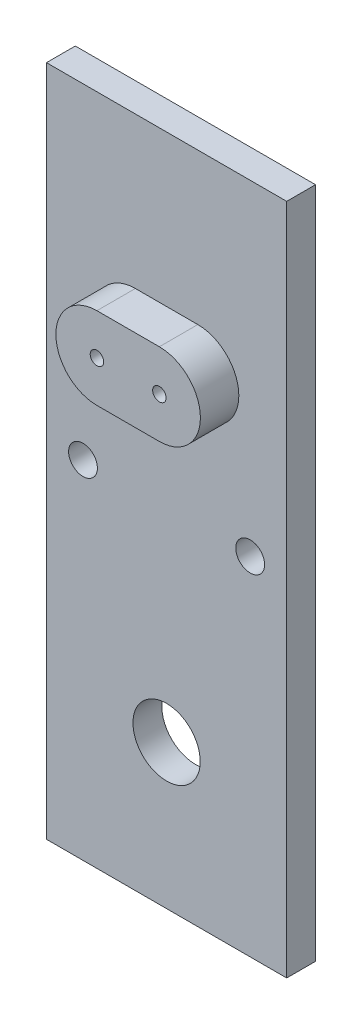
SolidWorks part; units mm, degrees
ref_plane "Front Plane" through (0, 0, 0) normal (0, 0, 1) x (1, 0, 0)
ref_plane "Top Plane" through (0, 0, 0) normal (0, 1, 0) x (1, 0, 0)
ref_plane "Right Plane" through (0, 0, 0) normal (1, 0, 0) x (0, 0, -1)
sketch "Sketch1" plane through (0, 0, 0) normal (0, 0, 1) x (1, 0, 0)
  line L0 (0, 0) -> (0, 18.7218) construction
  line L1 (-12.5, 35) -> (12.5, 35)
  line L2 (-12.5, 35) -> (-12.5, -35)
  line L3 (-12.5, -35) -> (12.5, -35)
  line L4 (12.5, 35) -> (12.5, -35)
  line L5 (-12.5, 35) -> (12.5, -35) construction
  line L6 (-12.5, -35) -> (12.5, 35) construction
  circle A0 centre (-8.7, 1.1) radius 1.5
  circle A1 centre (0, -20) radius 3.5
  circle A2 centre (8.7, 1.1) radius 1.5
  circle A3 centre (0, -20) radius 26 construction
  point P0 (0, 0)
  dimension "D3" = 3
  dimension "D4" = 7
  dimension "D7" = 15
  dimension "D8" = 52
  dimension "D1" = 25
  dimension "D2" = 70
  dimension "D5" = 21.1
  dimension "D6" = 17.4
extrude "Boss-Extrude1" add sketch "Sketch1" along normal blind 3
sketch "Sketch2" plane through (0, 0, 3) normal (0, 0, 1) x (1, 0, 0)
  circle A1 centre (0, -20) radius 26
sketch "Sketch3" plane through (0, 0, 3) normal (0, 0, 1) x (1, 0, 0)
  line L0 (0, 35) -> (0, 19.7026) construction
  line L1 (12.5, 35) -> (-12.5, 35) construction
  line L2 (-3.25, 15) -> (3.25, 15)
  circle A0 centre (-3.25, 15) radius 0.7
  circle A1 centre (3.25, 15) radius 0.7
  point P9 (0, 15)
  dimension "D1" = 1.4
  dimension "D2" = 6.5
  dimension "D3" = 20
extrude "Cut-Extrude1" cut sketch "Sketch3" against normal up to next
sketch "Sketch4" plane through (0, 0, 3) normal (0, 0, 1) x (1, 0, 0)
  line L0 (-3.25, 15) -> (3.25, 15) construction
  line L1 (-3.25, 19.2692) -> (3.25, 19.2692)
  line L2 (-3.25, 10.7308) -> (3.25, 10.7308)
  arc A0 (-3.25, 19.2692) -> (-3.25, 10.7308) centre (-3.25, 15) ccw
  arc A1 (3.25, 10.7308) -> (3.25, 19.2692) centre (3.25, 15) ccw
  circle A2 centre (-3.25, 15) radius 0.7
  circle A3 centre (3.25, 15) radius 0.7
  circle A4 centre (-3.25, 15) radius 0.7 construction
  point P4 (0, 15)
extrude "Boss-Extrude2" add sketch "Sketch4" along normal blind 4
